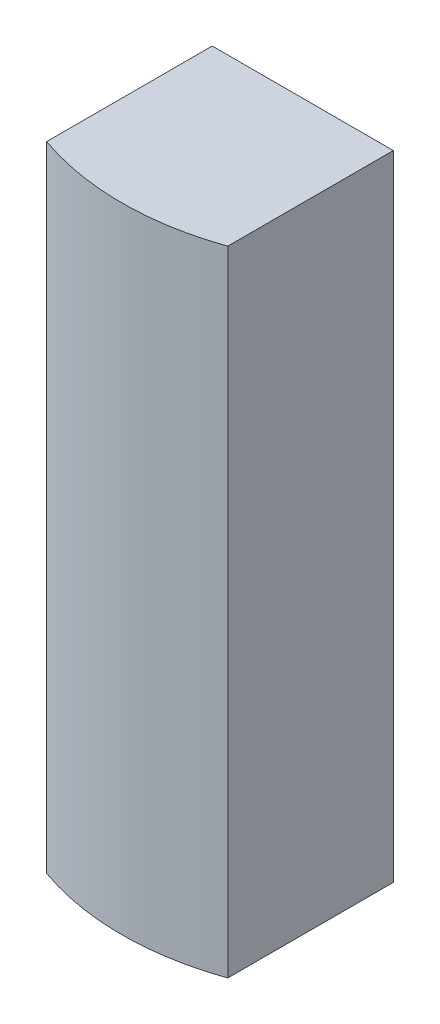
SolidWorks part; units mm, degrees
ref_plane "前视基准面" through (0, 0, 0) normal (0, 0, 1) x (1, 0, 0)
ref_plane "上视基准面" through (0, 0, 0) normal (0, 1, 0) x (1, 0, 0)
ref_plane "右视基准面" through (0, 0, 0) normal (1, 0, 0) x (0, 0, -1)
sketch "草图1" plane through (0, 0, 0) normal (0, 1, 0) x (1, 0, 0)
  line L0 (-56.5685, -20) -> (56.5685, -20)
  line L1 (-56.5685, 20) -> (56.5685, 20)
  line L2 (-20, 56.5685) -> (-20, -56.5685)
  line L3 (20, 56.5685) -> (20, -56.5685)
  circle A0 centre (0, 0) radius 60
  dimension "D1" = 120
  dimension "D2" = 20
  dimension "D3" = 20
  dimension "D4" = 20
  dimension "D5" = 20
extrude "凸台-拉伸1" add sketch "草图1" along normal blind 140 contours L2 A0 L3 L0
